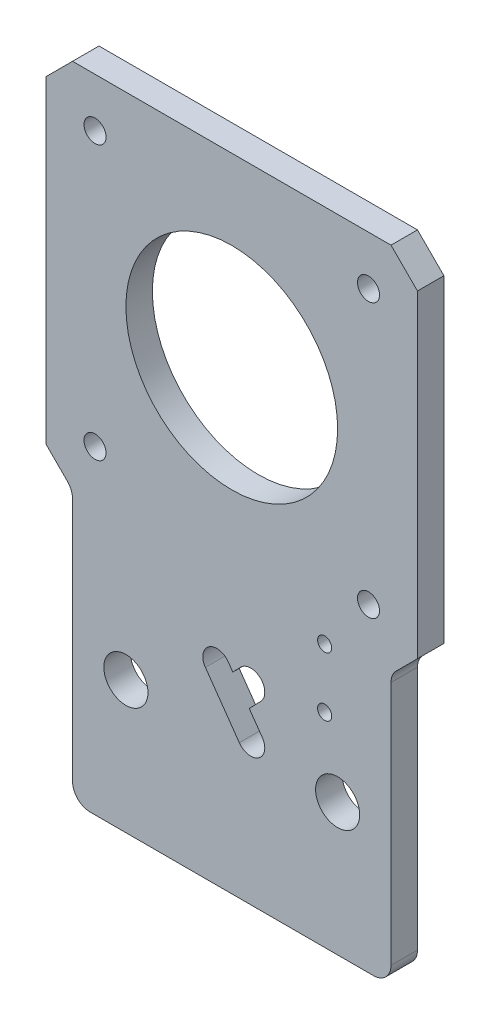
SolidWorks part; units mm, degrees
ref_plane "Plano frontal" through (0, 0, 0) normal (0, 0, 1) x (1, 0, 0)
ref_plane "Plano superior" through (0, 0, 0) normal (0, 1, 0) x (1, 0, 0)
ref_plane "Plano direito" through (0, 0, 0) normal (1, 0, 0) x (0, 0, -1)
sketch "Sketch1" plane through (0, 0, 0) normal (0, 0, 1) x (1, 0, 0)
  line L1 (-18.05, -21.05) -> (18.05, -21.05) construction
  line L2 (18.05, -51.655) -> (18.05, -21.05)
  line L4 (-18.05, -51.655) -> (-18.05, -21.05)
  line L5 (18.05, -51.655) -> (-18.05, -51.655)
  line L16 (-21.05, -18.05) -> (-18.05, -21.05)
  line L18 (18.05, -21.05) -> (21.05, -18.05)
  line L19 (21.05, -18.05) -> (21.05, 18.05)
  line L20 (21.05, 18.05) -> (18.05, 21.05)
  line L21 (18.05, 21.05) -> (-18.05, 21.05)
  line L22 (-18.05, 21.05) -> (-21.05, 18.05)
  line L23 (-21.05, 18.05) -> (-21.05, -18.05)
  circle A3 centre (0, 0) radius 12
  dimension "D2" = 36.1
  dimension "D3" = 4.2426
  dimension "D1" = 30.605
extrude "Boss-Extrude1" add sketch "Sketch1" along normal blind 3
hole_wizard "Tap Drill for M3 Tap1" positions "Sketch3" profile "Sketch2" hole size "M3" standard "ISO"
sketch "Sketch3" plane through (0, 0, 3) normal (0, 0, 1) x (1, 0, 0)
  point P0 (-15.5, 15.5)
  point P3 (15.5, 15.5)
  point P6 (-15.5, -15.5)
  point P9 (15.5, -15.5)
sketch "Sketch2" plane through (-15.5, 15.5, 3) normal (1, 0, 0) x (0, -1, 0)
  line L0 (0, 0) -> (0, 5.7511)
  line L1 (0, 5.7511) -> (1.25, 5)
  line L2 (1.25, 5) -> (1.25, 0)
  line L5 (1.25, 0) -> (0, 0)
  line L10 (0, 5.7511) -> (-1.25, 5) construction
  line L11 (0, -6.35) -> (0, 107.95) construction
  dimension "Hole Dia." = 2.5
  dimension "Hole Depth" = 5
  dimension "Drill Angle" = 118
hole_wizard "Tap Drill for M6 Tap1" positions "Sketch5" profile "Sketch4" hole size "M6" standard "ISO"
sketch "Sketch5" plane through (0, 0, 3) normal (0, 0, 1) x (1, 0, 0)
  line L1 (0, -51.655) -> (0, -21.05) construction
  line L2 (-18.05, -51.655) -> (18.05, -51.655) construction
  line L4 (-579.95, -36.655) -> (23.05, -36.655) construction
  point P28 (12, -36.655)
  point P32 (-12, -36.655)
sketch "Sketch4" plane through (-12, -36.655, 3) normal (1, 0, 0) x (0, -1, 0)
  line L0 (0, 0) -> (0, 6.5022)
  line L1 (0, 6.5022) -> (2.5, 5)
  line L2 (2.5, 5) -> (2.5, 0)
  line L5 (2.5, 0) -> (0, 0)
  line L10 (0, 6.5022) -> (-2.5, 5) construction
  line L11 (0, -6.35) -> (0, 107.95) construction
  dimension "Hole Dia." = 5
  dimension "Hole Depth" = 5
  dimension "Drill Angle" = 118
fillet "Fillet1" radius 2 4 edges at (18.05, -21.05, 1.5) (18.05, -51.655, 1.5) (-18.05, -51.655, 1.5) (-18.05, -21.05, 1.5)
hole_wizard "Tap Drill for M2 Tap1" positions "Sketch7" profile "Sketch6" hole size "M2" standard "ISO"
sketch "Sketch7" plane through (0, 0, 3) normal (0, 0, 1) x (1, 0, 0)
  point P0 (10.5295, -21.8613)
  point P3 (10.5295, -28.5613)
sketch "Sketch6" plane through (10.5295, -21.8613, 3) normal (1, 0, 0) x (0, -1, 0)
  line L0 (0, 0) -> (0, 5.4807)
  line L1 (0, 5.4807) -> (0.8, 5)
  line L2 (0.8, 5) -> (0.8, 0)
  line L5 (0.8, 0) -> (0, 0)
  line L10 (0, 5.4807) -> (-0.8, 5) construction
  line L11 (0, -6.35) -> (0, 107.95) construction
  dimension "Hole Dia." = 1.6
  dimension "Hole Depth" = 5
  dimension "Drill Angle" = 118
sketch "Sketch8" plane through (0, 0, 0) normal (0, 0, -1) x (-1, 0, 0)
  line L0 (8.6131, -51.655) -> (-8.6131, -51.655) construction
  line L1 (0, -51.655) -> (0, -33.8118) construction
  line L2 (2.9921, -30.9145) -> (-0.8553, -36.3863)
  line L3 (0.3948, -29.0883) -> (-0.1195, -29.8197)
  line L4 (-1.0138, -28.8967) -> (0, -29.943)
  line L5 (-3.294, -31.1061) -> (-1.9785, -32.4637)
  line L6 (-1.9785, -32.4637) -> (-3.4525, -34.5601)
  line L7 (0, -29.943) -> (0, -16.4461) construction
  arc A0 (2.9921, -30.9145) -> (0.3948, -29.0883) centre (1.6934, -30.0014) ccw
  arc A1 (-3.4525, -34.5601) -> (-0.8553, -36.3863) centre (-2.1539, -35.4732) ccw
  arc A2 (-1.0138, -28.8967) -> (-3.294, -31.1061) centre (-2.1539, -30.0014) ccw
  point P8 (-0.2302, -32.7373)
  point P13 (-1.077, -31.1128)
extrude "Cut-Extrude1" cut sketch "Sketch8" against normal blind 10
